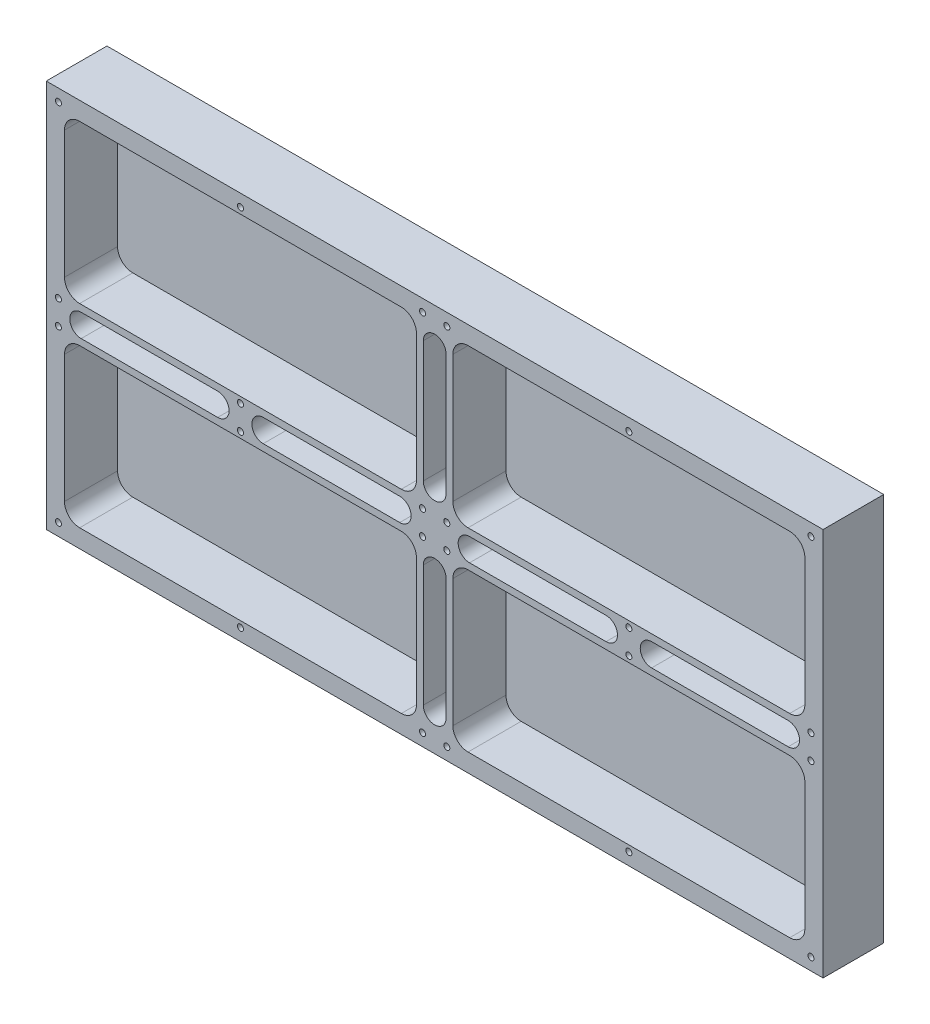
SolidWorks part; units mm, degrees
ref_plane "Ebene vorne" through (0, 0, 0) normal (0, 0, 1) x (1, 0, 0)
ref_plane "Ebene oben" through (0, 0, 0) normal (0, 1, 0) x (1, 0, 0)
ref_plane "Ebene rechts" through (0, 0, 0) normal (1, 0, 0) x (0, 0, -1)
sketch "Skizze1" plane through (0, 0, 0) normal (0, 0, 1) x (1, 0, 0)
  line L1 (0, 0) -> (512, 0)
  line L2 (0, 0) -> (0, 256)
  line L3 (0, 256) -> (512, 256)
  line L4 (512, 0) -> (512, 256)
  dimension "D1" = 512
  dimension "D2" = 256
extrude "Aufsatz-Linear austragen1" add sketch "Skizze1" along normal blind 40
sketch "Skizze2" plane through (0, 0, 40) normal (0, 0, 1) x (1, 0, 0)
  line L8 (12, 244) -> (12, 12)
  line L9 (12, 12) -> (500, 12)
  line L10 (500, 12) -> (500, 244)
  line L11 (500, 244) -> (12, 244)
  line L12 (12, 244) -> (12, 12)
  line L13 (12, 12) -> (500, 12)
  line L14 (500, 12) -> (500, 244)
  line L15 (500, 244) -> (12, 244)
  dimension "D1" = 12
extrude "Schnitt-Linear austragen1" cut sketch "Skizze2" against normal blind 35
sketch "Skizze5" plane through (0, 0, 5) normal (0, 0, 1) x (1, 0, 0)
  line L0 (0, 128) -> (50000, 128) construction
  line L1 (0, 256) -> (0, 0) construction
  line L2 (512, 0) -> (512, 256) construction
  line L3 (256, 256) -> (256, 128) construction
  line L4 (512, 256) -> (0, 256) construction
  line L5 (12, 244) -> (12, 12) construction
  line L6 (12, 140) -> (244, 140)
  line L7 (12, 140) -> (12, 116)
  line L8 (12, 116) -> (244, 116)
  line L9 (500, 140) -> (500, 116)
  line L10 (500, 12) -> (500, 244) construction
  line L11 (500, 244) -> (12, 244) construction
  line L12 (244, 244) -> (268, 244)
  line L13 (244, 244) -> (244, 140)
  line L14 (244, 12) -> (268, 12)
  line L15 (268, 244) -> (268, 140)
  line L16 (12, 12) -> (500, 12) construction
  line L17 (244, 116) -> (244, 12)
  line L18 (256, 128) -> (256, -49744) construction
  line L19 (268, 116) -> (268, 12)
  line L20 (268, 140) -> (500, 140)
  line L21 (268, 116) -> (500, 116)
  point P4 (0, 128)
  point P7 (512, 128)
  point P12 (256, 256)
  point P30 (0, 0)
  dimension "D1" = 24
  dimension "D2" = 24
extrude "Aufsatz-Linear austragen2" add sketch "Skizze5" along normal up to surface (35 mm away) up to face at (256, 128, 40)
hole_wizard "Stirnsenkung für M3 Zylinderschraube mit Innensechskant1" positions "Skizze3" profile "Skizze4" counterbore size "M3" standard "DIN" end condition through all
sketch "Skizze3" plane through (0, 0, 0) normal (0, 0, 1) x (1, 0, 0)
  line L1 (512, 256) -> (0, 256) construction
  line L2 (8, 248) -> (0, 248) construction
  line L3 (0, 256) -> (0, 0) construction
  line L5 (248, 248) -> (256, 248) construction
  line L8 (256, 256) -> (256, -49744) construction
  line L9 (0, 128) -> (50000, 128) construction
  line L10 (504, 248) -> (512, 248) construction
  line L11 (504, 8) -> (512, 8) construction
  line L12 (248, 8) -> (256, 8) construction
  line L13 (8, 8) -> (0, 8) construction
  line L14 (14.5287, 192) -> (50014.5287, 192) construction
  line L15 (12, 244) -> (12, 140) construction
  line L16 (12, 64) -> (50012, 64) construction
  line L17 (12, 116) -> (12, 12) construction
  line L18 (504, 136) -> (512, 136) construction
  line L19 (248, 136) -> (256, 136) construction
  line L20 (8, 136) -> (0, 136) construction
  line L21 (8, 120) -> (0, 120) construction
  line L22 (248, 120) -> (256, 120) construction
  line L23 (504, 120) -> (512, 120) construction
  point P0 (8, 248)
  point P7 (128, 248)
  point P9 (248, 248)
  point P28 (256, 256)
  point P31 (0, 128)
  point P35 (264, 248)
  point P36 (384, 248)
  point P43 (384, 8)
  point P44 (264, 8)
  point P45 (128, 8)
  point P49 (504, 248)
  point P52 (504, 8)
  point P56 (8, 8)
  point P63 (12, 192)
  point P68 (12, 64)
  point P75 (384, 136)
  point P76 (264, 136)
  point P77 (128, 136)
  point P84 (128, 120)
  point P85 (264, 120)
  point P86 (384, 120)
  point P89 (248, 136)
  point P92 (248, 120)
  point P95 (248, 8)
  point P98 (504, 136)
  point P101 (504, 120)
  point P104 (8, 136)
  point P107 (8, 120)
  dimension "D2" = 8
  dimension "D3" = 120
  dimension "D4" = 120
sketch "Skizze4" plane through (8, 248, 0) normal (1, 0, 0) x (0, 1, 0)
  line L0 (0, 0) -> (0, 40)
  line L1 (0, 40) -> (2, 40)
  line L3 (2, 40) -> (2, 3.4)
  line L4 (2, 3.4) -> (3.25, 3.4)
  line L5 (3.25, 3.4) -> (3.25, 0)
  line L7 (3.25, 0) -> (0, 0)
  line L11 (0, -6.35) -> (0, 107.95) construction
  dimension "Bohrerdurchmesser" = 4
  dimension "Bohrungstiefe" = 40
  dimension "Senkdurchmesser2" = 6.5
  dimension "Senktiefe2" = 3.4
ref_plane "Ebene1" through (0, 192, 0) normal (0, 1, 0) x (1, 0, 0)
ref_plane "Ebene2" through (0, 0, 0) normal (0, -1, 0) x (-1, 0, 0)
fillet "Verrundung1" radius 10 16 edges at (12, 140, 22.5) (268, 140, 22.5) (268, 244, 22.5) (268, 116, 22.5) (268, 12, 22.5) (500, 12, 22.5) (500, 116, 22.5) (500, 244, 22.5) (244, 244, 22.5) (12, 116, 22.5) (12, 12, 22.5) (244, 12, 22.5) (244, 116, 22.5) (244, 140, 22.5) (12, 244, 22.5) (500, 140, 22.5)
sketch "Skizze6" plane through (0, 0, 40) normal (0, 0, 1) x (1, 0, 0)
  line L0 (489, 128) -> (399, 128) construction
  line L1 (489, 120.5) -> (399, 120.5)
  line L2 (489, 135.5) -> (399, 135.5)
  arc A0 (489, 120.5) -> (489, 135.5) centre (489, 128) ccw
  arc A1 (399, 135.5) -> (399, 120.5) centre (399, 128) ccw
  circle A2 centre (384, 136) radius 2 construction
  circle A3 centre (504, 136) radius 2 construction
  point P2 (444, 128)
  point P11 (0, 0)
  dimension "D1" = 15
  dimension "D2" = 15
  dimension "D3" = 15
  dimension "D4" = 8
extrude "Schnitt-Linear austragen2" cut sketch "Skizze6" against normal up to surface (35 mm away) up to face at (128, 192, 5)
sketch "Skizze7" plane through (0, 0, 40) normal (0, 0, 1) x (1, 0, 0)
  line L0 (324, 128) -> (384, 128) construction
  line L1 (384, 136) -> (384, 120) construction
  line L2 (264, 136) -> (264, 120) construction
  line L3 (264, 128) -> (324, 128) construction
  point P0 (324, 128)
  point P24 (0, 0)
pattern_sketch "Skizzen-Muster1" of "Schnitt-Linear austragen2" driven by "Skizze7"
ref_plane "Ebene3" through (256, 0, 0) normal (-1, 0, 0) x (0, 0, 1)
mirror "Spiegeln7" about plane through (256, 0, 0) normal (-1, 0, 0) of "Schnitt-Linear austragen2", "Skizzen-Muster1"
sketch "Skizze9" plane through (0, 0, 40) normal (0, 0, 1) x (1, 0, 0)
  line L0 (256, 232) -> (256, 152) construction
  line L1 (263.5, 232) -> (263.5, 152)
  line L2 (248.5, 232) -> (248.5, 152)
  line L3 (248, 248) -> (264, 248) construction
  line L4 (248, 136) -> (264, 136) construction
  line L5 (256, 248) -> (256, 232) construction
  line L6 (256, 136) -> (256, 152) construction
  arc A0 (263.5, 232) -> (248.5, 232) centre (256, 232) ccw
  arc A1 (248.5, 152) -> (263.5, 152) centre (256, 152) ccw
  point P2 (256, 192)
  dimension "D1" = 15
  dimension "D2" = 80
extrude "Schnitt-Linear austragen3" cut sketch "Skizze9" against normal up to surface (35 mm away) up to face at (128, 192, 5)
ref_plane "Ebene4" through (0, 128, 0) normal (0, 1, 0) x (1, 0, 0)
mirror "Spiegeln8" about plane through (0, 128, 0) normal (0, 1, 0) of "Schnitt-Linear austragen3"
